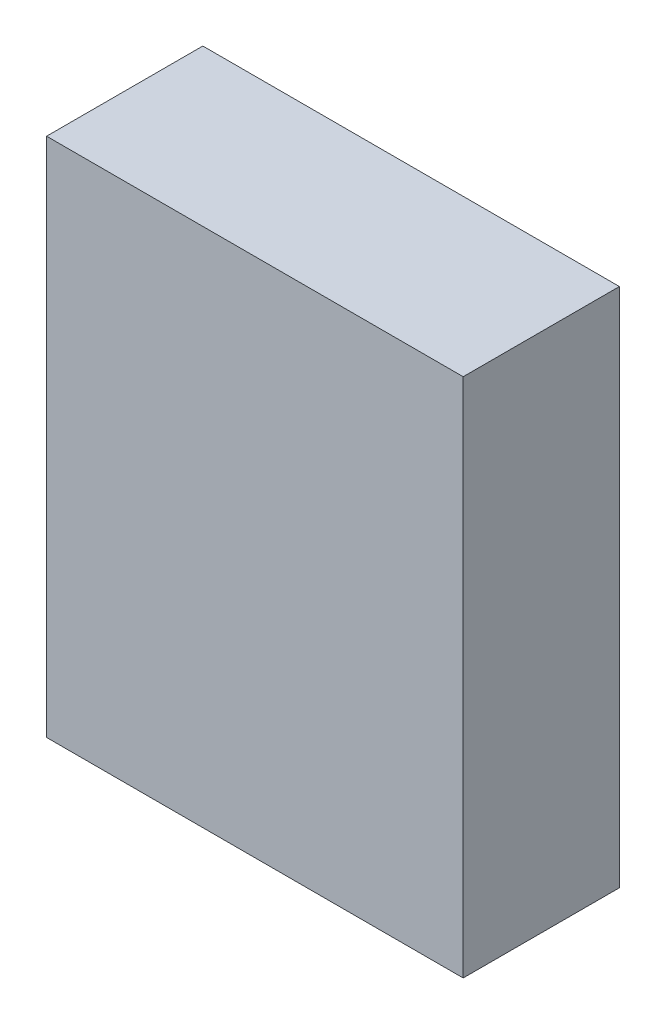
SolidWorks part; units mm, degrees
material "Low Carbon Steel"
ref_plane "Front Plane" through (0, 0, 0) normal (0, 0, 1) x (1, 0, 0)
ref_plane "Top Plane" through (0, 0, 0) normal (0, 1, 0) x (1, 0, 0)
ref_plane "Right Plane" through (0, 0, 0) normal (1, 0, 0) x (0, 0, -1)
sketch "Sketch1" plane through (0, 0, 0) normal (0, 0, 1) x (1, 0, 0)
  line L0 (50.8, 63.5) -> (-50.8, -63.5) construction
  line L1 (-50.8, 63.5) -> (50.8, 63.5)
  line L2 (-50.8, 63.5) -> (-50.8, -63.5)
  line L3 (-50.8, -63.5) -> (50.8, -63.5)
  line L4 (50.8, 63.5) -> (50.8, -63.5)
  dimension "D1" = 127
  dimension "D2" = 101.6
extrude "Boss-Extrude1" add sketch "Sketch1" along normal blind 38.1
other "Freeze***"
